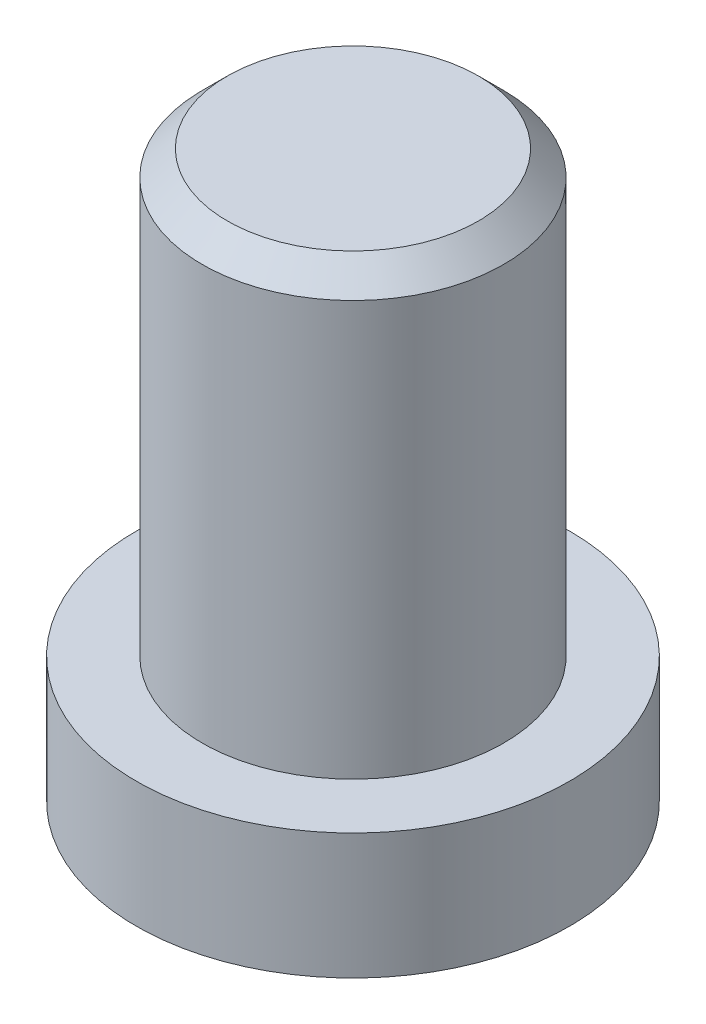
SolidWorks part; units mm, degrees
ref_plane "Front Plane" through (0, 0, 0) normal (0, 0, 1) x (1, 0, 0)
ref_plane "Top Plane" through (0, 0, 0) normal (0, 1, 0) x (1, 0, 0)
ref_plane "Right Plane" through (0, 0, 0) normal (1, 0, 0) x (0, 0, -1)
sketch "Sketch2" plane through (0, 0, 0) normal (0, 1, 0) x (1, 0, 0)
  circle A0 centre (0, 0) radius 1.2
  dimension "D1" = 2.4
extrude "Boss-Extrude1" add sketch "Sketch2" along normal blind 4.5
sketch "Sketch5" plane through (0, 0, 0) normal (0, -1, 0) x (1, 0, 0)
  circle A0 centre (0, 0) radius 1.725
  dimension "D1" = 3.45
extrude "Boss-Extrude2" add sketch "Sketch5" against normal blind 1
chamfer "Chamfer1" distance 0.2 angle 45 1 edges at (0, 4.5, 1.2)
